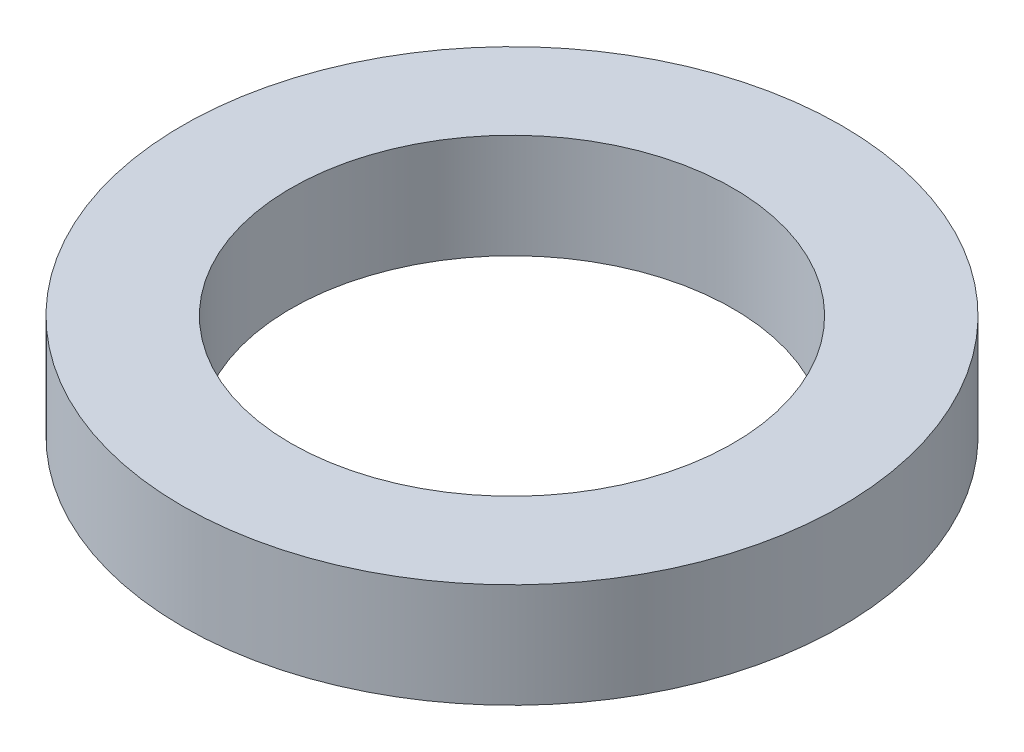
SolidWorks part; units mm, degrees
ref_plane "前视基准面" through (0, 0, 0) normal (0, 0, 1) x (1, 0, 0)
ref_plane "上视基准面" through (0, 0, 0) normal (0, 1, 0) x (1, 0, 0)
ref_plane "右视基准面" through (0, 0, 0) normal (1, 0, 0) x (0, 0, -1)
ref_plane "基准面4" through (0, 0, 0) normal (0, 0, -1) x (-1, 0, 0)
sketch "草图1" plane through (0, 0, 0) normal (0, 0, -1) x (-1, 0, 0)
  line L0 (-6, 1.9) -> (-6, 0)
  line L1 (-6, 0) -> (-4.025, 0)
  line L2 (-4.025, 0) -> (-4.025, 1.9)
  line L3 (-4.025, 1.9) -> (-6, 1.9)
  line L4 (0, 0) -> (0, 1.9) construction
revolve "旋转1" add sketch "草图1" angle 360 about L4
